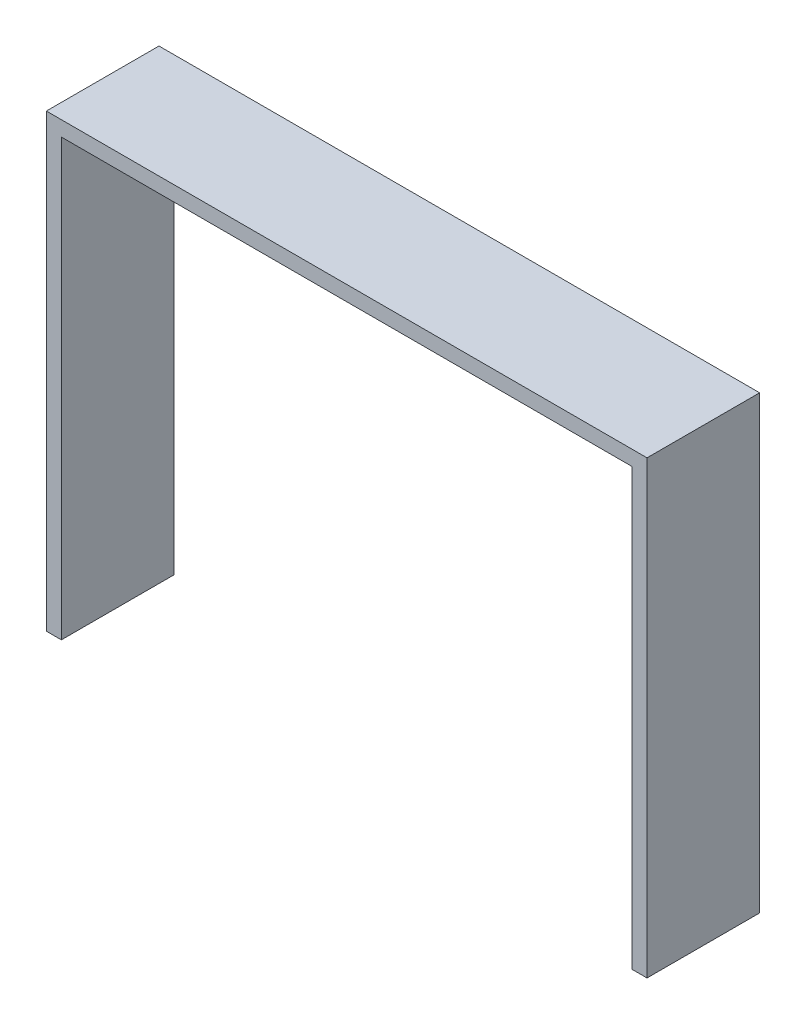
SolidWorks part; units mm, degrees
material "PE High Density"
ref_plane "Front Plane" through (0, 0, 0) normal (1, 0, 0) x (0, 1, 0)
ref_plane "Top Plane" through (0, 0, 0) normal (0, 0, 1) x (0, 1, 0)
ref_plane "Right Plane" through (0, 0, 0) normal (0, 1, 0) x (-1, 0, 0)
sketch "Sketch2" plane through (0, 0, 0) normal (0, 0, 1) x (0, 1, 0)
  line L0 (-30, -38) -> (-30, -40)
  line L1 (-30, 40) -> (30, 40)
  line L2 (-30, 40) -> (-30, 38)
  line L3 (-30, -40) -> (30, -40)
  line L4 (30, 40) -> (30, -40)
  line L5 (-30, 40) -> (30, -40) construction
  line L6 (-30, -40) -> (30, 40) construction
  line L7 (28, 38) -> (-30, 38)
  line L8 (28, 38) -> (28, -38)
  line L9 (28, -38) -> (-30, -38)
  point P0 (0, 0)
  dimension "D1" = 80
  dimension "D2" = 60
  dimension "D3" = 2
  dimension "D4" = 2
  dimension "D5" = 2
extrude "Boss-Extrude1" add sketch "Sketch2" against normal blind 15
scale "Scale1" scale about centroid uniform scaling yes scale factor 0.7
